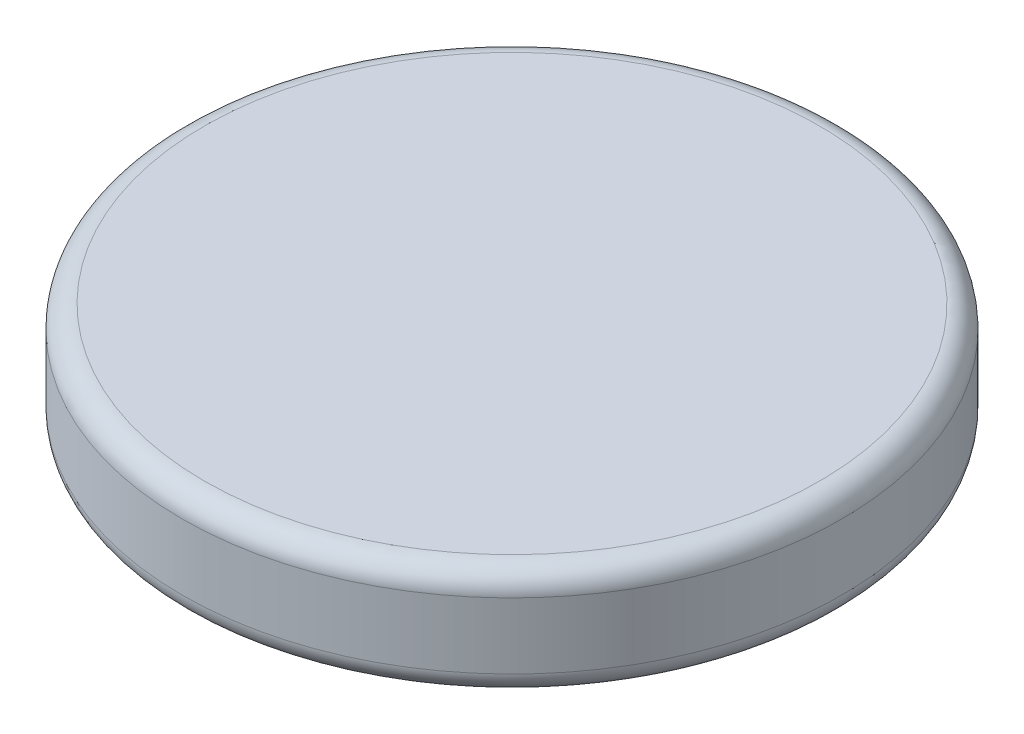
SolidWorks part; units mm, degrees
ref_plane "Front" through (0, 0, 0) normal (0, 0, 1) x (1, 0, 0)
ref_plane "Top" through (0, 0, 0) normal (0, 1, 0) x (1, 0, 0)
ref_plane "Right" through (0, 0, 0) normal (1, 0, 0) x (0, 0, -1)
sketch "Эскиз1" plane through (0, 0, 0) normal (0, 1, 0) x (1, 0, 0)
  circle A0 centre (0, 0) radius 3
  dimension "D1" = 6
extrude "Бобышка-Вытянуть1" add sketch "Эскиз1" along normal blind 1
fillet "Скругление1" radius 0.2 2 edges at (0, 0, 3) (0, 1, 3)
